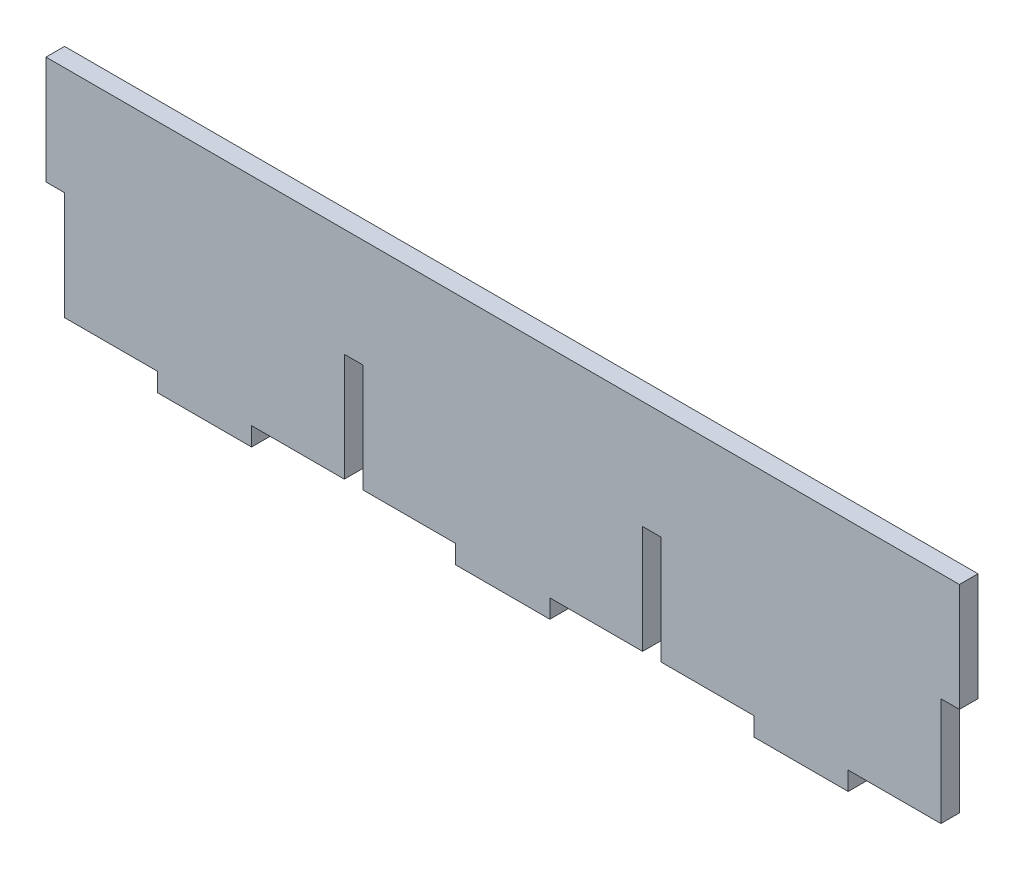
SolidWorks part; units mm, degrees
ref_plane "Front Plane" through (0, 0, 0) normal (0, 0, 1) x (1, 0, 0)
ref_plane "Top Plane" through (0, 0, 0) normal (0, 1, 0) x (1, 0, 0)
ref_plane "Right Plane" through (0, 0, 0) normal (1, 0, 0) x (0, 0, -1)
sketch "Sketch1" plane through (0, 0, 0) normal (0, 0, 1) x (1, 0, 0)
  line L0 (73.875, 1.5) -> (70.875, 1.5)
  line L1 (-73.875, -19) -> (73.875, -19)
  line L2 (-73.875, -19) -> (-73.875, 19)
  line L3 (-73.875, 19) -> (73.875, 19)
  line L4 (73.875, -19) -> (73.875, 19)
  line L5 (-73.875, -19) -> (73.875, 19) construction
  line L6 (-73.875, 19) -> (73.875, -19) construction
  line L7 (70.875, 1.5) -> (70.875, -19)
  line L8 (70.875, -19) -> (25.625, -19)
  line L9 (25.625, -19) -> (25.625, 1.5)
  line L10 (25.625, 1.5) -> (22.625, 1.5)
  line L11 (22.625, 1.5) -> (22.625, -19)
  line L12 (22.625, -19) -> (-22.625, -19)
  line L13 (-22.625, -19) -> (-22.625, 1.5)
  line L14 (-22.625, 1.5) -> (-25.625, 1.5)
  line L15 (-25.625, 1.5) -> (-25.625, -19)
  line L16 (-73.875, 1.5) -> (-70.875, 1.5)
  line L17 (-70.875, 1.5) -> (-70.875, -19)
  line L18 (-25.625, -16) -> (-40.625, -16)
  line L19 (-40.625, -16) -> (-40.625, -19)
  line L20 (-40.625, -19) -> (-55.875, -19)
  line L21 (-55.875, -19) -> (-55.875, -16)
  line L22 (-55.875, -16) -> (-70.875, -16)
  line L23 (-22.625, -16) -> (-7.625, -16)
  line L24 (-7.625, -16) -> (-7.625, -19)
  line L25 (-7.625, -19) -> (7.625, -19)
  line L26 (7.625, -19) -> (7.625, -16)
  line L27 (7.625, -16) -> (22.625, -16)
  line L28 (25.625, -16) -> (40.625, -16)
  line L29 (40.625, -16) -> (40.625, -19)
  line L30 (70.875, -16) -> (55.875, -16)
  line L31 (55.875, -16) -> (55.875, -19)
  point P0 (0, 0)
  dimension "D1" = 38
  dimension "D2" = 147.75
  dimension "D3" = 3
  dimension "D4" = 45.25
  dimension "D5" = 3
  dimension "D6" = 45.25
  dimension "D7" = 3
  dimension "D8" = 3
  dimension "D9" = 15
  dimension "D10" = 15
  dimension "D11" = 3
  dimension "D12" = 3
  dimension "D13" = 15
  dimension "D14" = 15
  dimension "D15" = 15
  dimension "D16" = 15
  dimension "D17" = 17.5
  dimension "D18" = 17.5
  dimension "D19" = 3
extrude "Boss-Extrude1" add sketch "Sketch1" along normal blind 3 contours L16 L17 L1 L15 L14 L13 L11 L10 L9 L7 L0 L4 L3 L2
